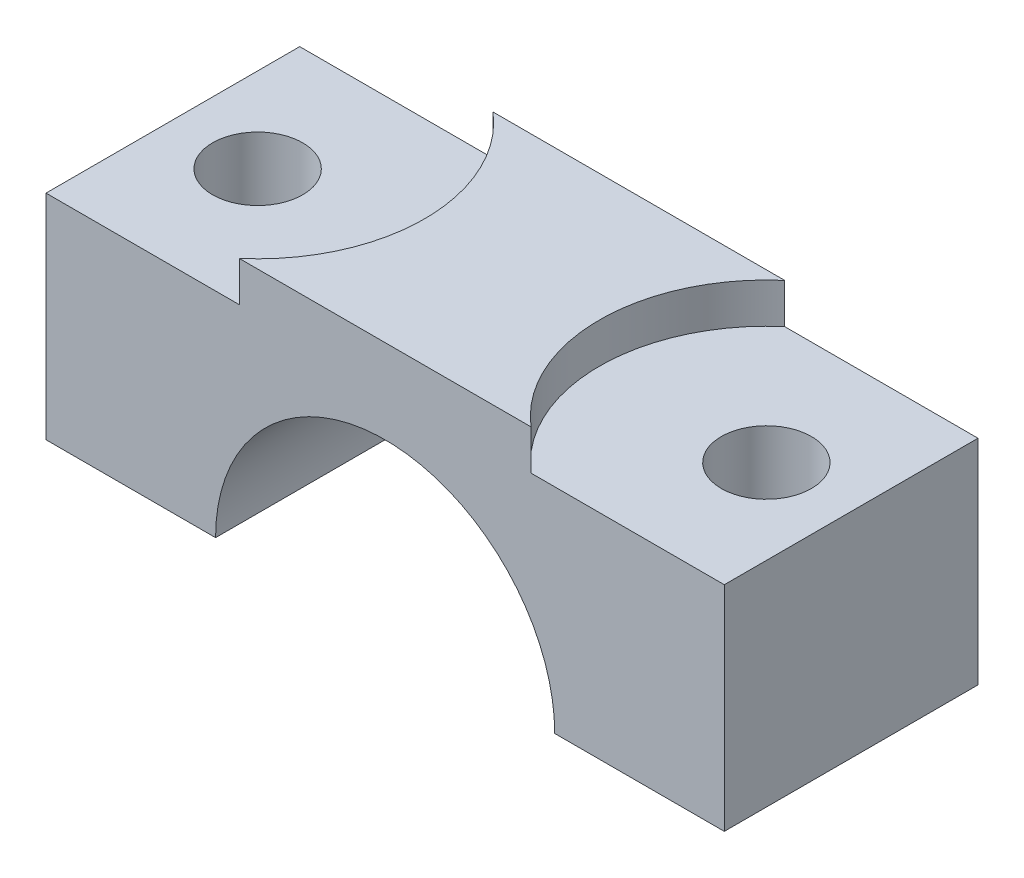
SolidWorks part; units mm, degrees
material "Alloy Steel"
ref_plane "Front Plane" through (0, 0, 0) normal (0, 0, 1) x (1, 0, 0)
ref_plane "Top Plane" through (0, 0, 0) normal (0, 1, 0) x (1, 0, 0)
ref_plane "Right Plane" through (0, 0, 0) normal (1, 0, 0) x (0, 0, -1)
sketch "Sketch2" plane through (0, 0, 0) normal (0, 0, 1) x (1, 0, 0)
  line L0 (12.7, 0) -> (25.4, 0)
  line L1 (-25.4, 0) -> (-12.7, 0)
  line L2 (-25.4, 0) -> (-25.4, 19)
  line L3 (-25.4, 19) -> (25.4, 19)
  line L4 (25.4, 0) -> (25.4, 19)
  arc A0 (-12.7, 0) -> (12.7, 0) centre (0, 0) cw
  point P4 (0, 19)
  dimension "D3" = 12.7
  dimension "D1" = 19
  dimension "D2" = 50.8
extrude "Boss-Extrude1" add sketch "Sketch2" along normal mid plane 19
sketch "Sketch3" plane through (0, 0, 0) normal (0, -1, 0) x (1, 0, 0)
  line L0 (-25.4, 0) -> (-12.7, 0) construction
  line L1 (-25.4, 9.5) -> (-25.4, -9.5) construction
  line L2 (-12.7, 9.5) -> (-12.7, -9.5) construction
  line L3 (12.7, 0) -> (25.4, 0) construction
  line L4 (12.7, 9.5) -> (12.7, -9.5) construction
  line L5 (25.4, 9.5) -> (25.4, -9.5) construction
hole_wizard "CBORE for M12 Hex Head Cap Screw1" positions "Sketch5" profile "Sketch6" counterbore size "M12" standard "ISO" end condition through all
sketch "Sketch5" plane through (0, 19, 0) normal (0, 1, 0) x (1, 0, 0)
  line L0 (-25.4, 0) -> (-12.7, 0) construction
  line L1 (12.7, 0) -> (25.4, 0) construction
  point P0 (-19.05, 0)
  point P4 (19.05, 0)
sketch "Sketch6" plane through (-19.05, 19, 0) normal (1, 0, 0) x (0, 0, 1)
  line L0 (0, 0) -> (0, 19)
  line L1 (0, 19) -> (3.375, 19)
  line L3 (3.375, 19) -> (3.375, 3)
  line L4 (3.375, 3) -> (12.5, 3)
  line L5 (12.5, 3) -> (12.5, 0)
  line L7 (12.5, 0) -> (0, 0)
  line L11 (0, -6.35) -> (0, 107.95) construction
  dimension "Thru Hole Dia." = 6.75
  dimension "Thru Hole Depth" = 19
  dimension "C'Bore Dia." = 25
  dimension "C'Bore Depth" = 3
